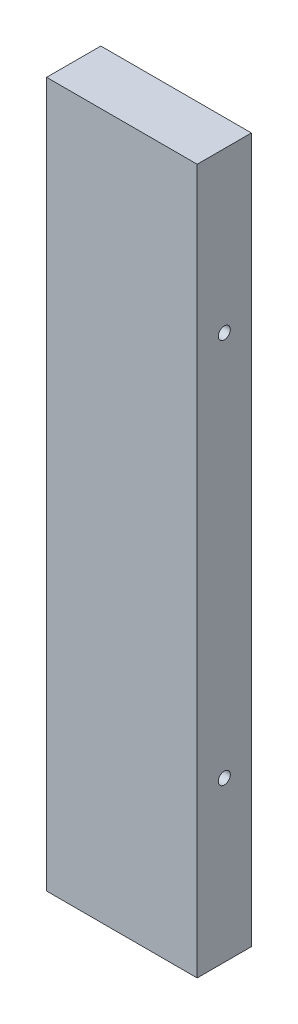
SolidWorks part; units mm, degrees
ref_plane "Front Plane" through (0, 0, 0) normal (0, 0, 1) x (1, 0, 0)
ref_plane "Top Plane" through (0, 0, 0) normal (0, 1, 0) x (1, 0, 0)
ref_plane "Right Plane" through (0, 0, 0) normal (1, 0, 0) x (0, 0, -1)
sketch "Sketch1" plane through (0, 0, 0) normal (0, 0, 1) x (1, 0, 0)
  line L1 (-25, 117) -> (25, 117)
  line L2 (-25, 117) -> (-25, -117)
  line L3 (-25, -117) -> (25, -117)
  line L4 (25, 117) -> (25, -117)
  line L5 (-25, 117) -> (25, -117) construction
  line L6 (-25, -117) -> (25, 117) construction
  point P0 (0, 0)
  dimension "D1" = 234
  dimension "D2" = 50
extrude "Boss-Extrude1" add sketch "Sketch1" along normal blind 18
hole_wizard "Ø4.0 (4) Diameter Hole2" positions "Sketch5" profile "Sketch4" hole size "Ø4.0" standard "ISO"
sketch "Sketch5" plane through (25, 0, 0) normal (1, 0, 0) x (0, 0, -1)
  point P0 (-9, 64)
  point P3 (-9, -64)
sketch "Sketch4" plane through (25, 64, 9) normal (0, 1, 0) x (0, 0, -1)
  line L0 (0, 0) -> (0, 31.2017)
  line L1 (0, 31.2017) -> (2, 30)
  line L2 (2, 30) -> (2, 0)
  line L5 (2, 0) -> (0, 0)
  line L10 (0, 31.2017) -> (-2, 30) construction
  line L11 (0, -6.35) -> (0, 107.95) construction
  dimension "Hole Dia." = 4
  dimension "Hole Depth" = 30
  dimension "Drill Angle" = 118
hole_wizard "Ø4.0 (4) Diameter Hole3" positions "Sketch7" profile "Sketch6" hole size "Ø4.0" standard "ISO"
sketch "Sketch7" plane through (-25, 0, 0) normal (-1, 0, 0) x (0, 0, 1)
  point P0 (9, 85)
  point P3 (9, 0)
  point P6 (9, -85)
sketch "Sketch6" plane through (-25, 85, 9) normal (0, 1, 0) x (0, 0, 1)
  line L0 (0, 0) -> (0, 31.2017)
  line L1 (0, 31.2017) -> (2, 30)
  line L2 (2, 30) -> (2, 0)
  line L5 (2, 0) -> (0, 0)
  line L10 (0, 31.2017) -> (-2, 30) construction
  line L11 (0, -6.35) -> (0, 107.95) construction
  dimension "Hole Dia." = 4
  dimension "Hole Depth" = 30
  dimension "Drill Angle" = 118
